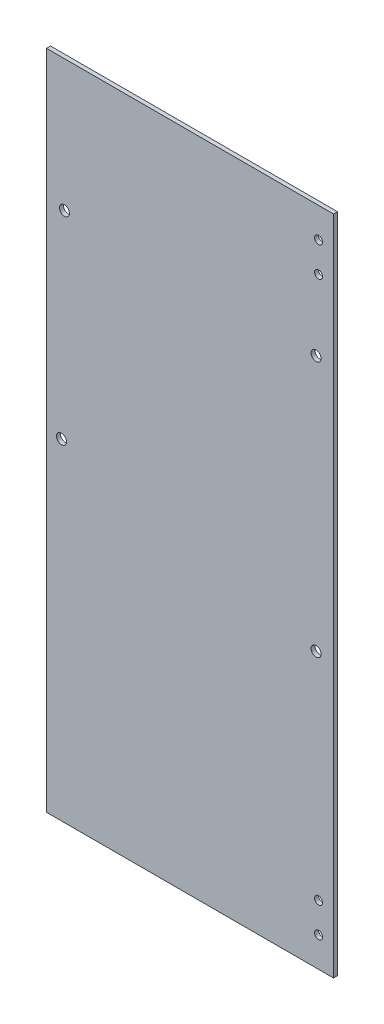
SolidWorks part; units mm, degrees
ref_plane "前视基准面" through (0, 0, 0) normal (0, 0, 1) x (1, 0, 0)
ref_plane "上视基准面" through (0, 0, 0) normal (0, 1, 0) x (1, 0, 0)
ref_plane "右视基准面" through (0, 0, 0) normal (1, 0, 0) x (0, 0, -1)
other "Configuration Table"
sketch "草图1" plane through (0, 0, 0) normal (0, 0, 1) x (1, 0, 0)
  line L1 (0, 0) -> (144, 0)
  line L2 (0, 0) -> (0, -332)
  line L3 (0, -332) -> (144, -332)
  line L4 (144, 0) -> (144, -332)
extrude "凸台-拉伸1" add sketch "草图1" along normal blind 2
sketch "草图2" plane through (0, 0, 2) normal (0, 0, 1) x (1, 0, 0)
  line L0 (3, -60) -> (141.26, -60) construction
  line L4 (3, -60) -> (3, -200.4) construction
  line L5 (3, -200.4) -> (141.26, -200.4) construction
  line L6 (141.26, -200.4) -> (141.26, -60) construction
  line L7 (3, -130.2) -> (141.26, -130.2) construction
  line L8 (72.13, -60) -> (72.13, -200.4) construction
  circle A0 centre (9, -66) radius 2.5
  circle A1 centre (135.26, -66) radius 2.5
  circle A3 centre (135.26, -194.4) radius 2.5
  dimension "D1" = 6
  dimension "D2" = 6
  dimension "D3" = 6
  dimension "D4" = 6
extrude "切除-拉伸1" cut sketch "草图2" against normal blind 2
sketch "草图4" plane through (0, 0, 0) normal (0, 0, -1) x (-1, 0, 0)
  line L0 (-144, 0) -> (0, 0) construction
  line L1 (-144, -332) -> (-144, 0) construction
  line L2 (-144, -166) -> (0, -166) construction
  line L3 (0, 0) -> (0, -332) construction
  circle A0 centre (-136.5, -15) radius 2
  circle A1 centre (-136.5, -30) radius 2
  circle A2 centre (-136.5, -302) radius 2
  circle A3 centre (-136.5, -317) radius 2
  circle A4 centre (-7.5, -166) radius 2.5
  dimension "D1" = 15
  dimension "D3" = 15
  dimension "D4" = 7.5
  dimension "D2" = 7.5
extrude "切除-拉伸2" cut sketch "草图4" against normal blind 10
